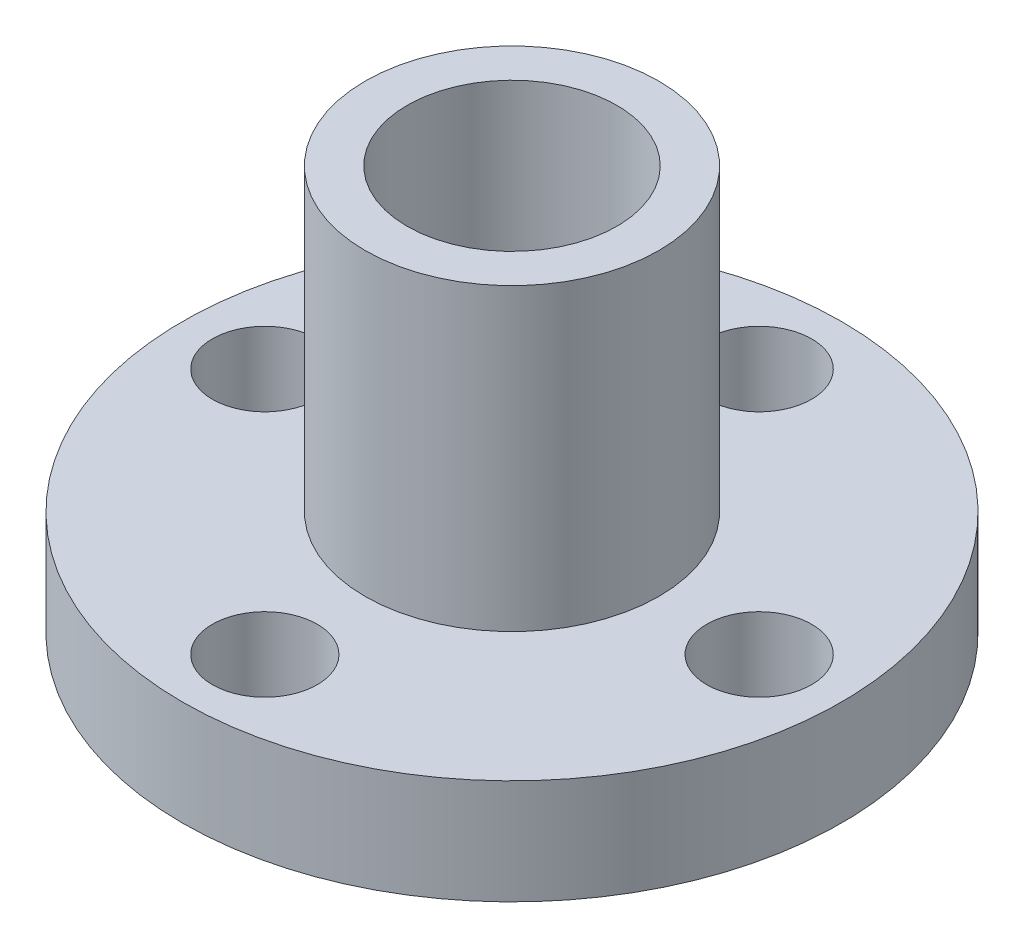
SolidWorks part; units mm, degrees
ref_plane "Alzado" through (0, 0, 0) normal (0, 0, 1) x (1, 0, 0)
ref_plane "Planta" through (0, 0, 0) normal (0, 1, 0) x (1, 0, 0)
ref_plane "Vista lateral" through (0, 0, 0) normal (1, 0, 0) x (0, 0, -1)
sketch "Croquis1" plane through (0, 0, 0) normal (0, 1, 0) x (1, 0, 0)
  line L0 (-8.25, 0) -> (8.25, 0)
  line L1 (0, -8.25) -> (0, 8.25)
  circle A0 centre (0, 0) radius 11
  circle A1 centre (0, 0) radius 3.5
  circle A2 centre (8.25, 0) radius 1.75
  circle A3 centre (0, 8.25) radius 1.75
  circle A4 centre (-8.25, 0) radius 1.75
  circle A5 centre (0, -8.25) radius 1.75
  point P7 (0, 0)
  point P10 (0, 0)
  dimension "D1" = 22
  dimension "D2" = 7
  dimension "D5" = 3.5
  dimension "D6" = 3.5
  dimension "D7" = 3.5
  dimension "D8" = 3.5
  dimension "D3" = 16.5
  dimension "D4" = 16.5
extrude "Saliente-Extruir1" add sketch "Croquis1" along normal blind 3.5
sketch "Croquis2" plane through (0, 3.5, 0) normal (0, 1, 0) x (1, 0, 0)
  circle A0 centre (0, 0) radius 3.5
  circle A1 centre (0, 0) radius 4.9
  dimension "D1" = 9.8
extrude "Saliente-Extruir2" add sketch "Croquis2" along normal blind 10
